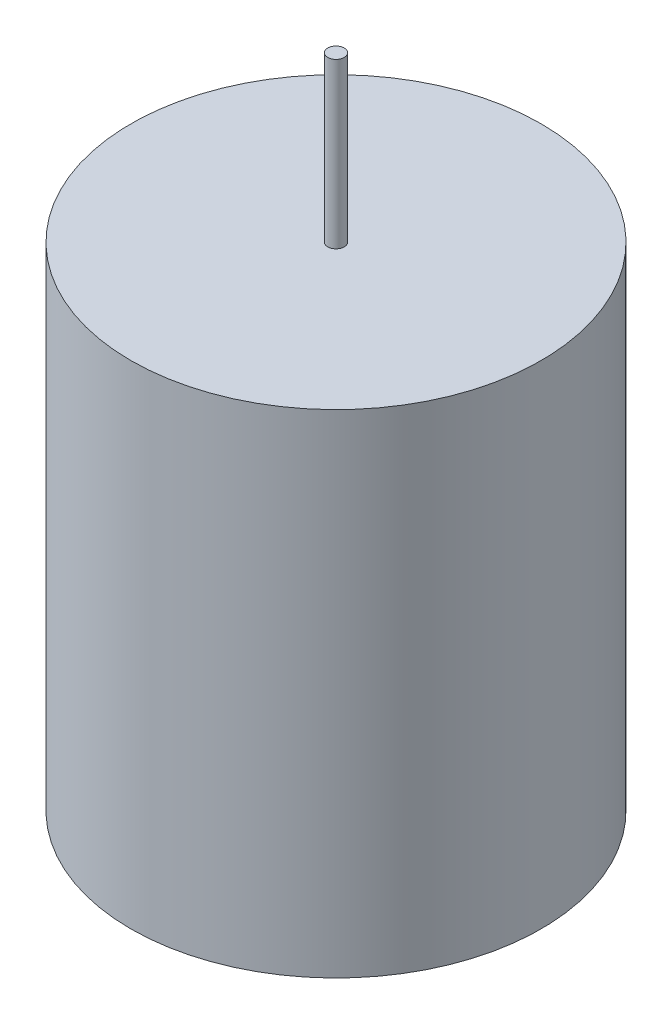
SolidWorks part; units mm, degrees
ref_plane "Front Plane" through (0, 0, 0) normal (0, 0, 1) x (1, 0, 0)
ref_plane "Top Plane" through (0, 0, 0) normal (0, 1, 0) x (1, 0, 0)
ref_plane "Right Plane" through (0, 0, 0) normal (1, 0, 0) x (0, 0, -1)
sketch "Sketch1" plane through (0, 0, 0) normal (0, 1, 0) x (1, 0, 0)
  circle A0 centre (0, 0) radius 12.5
  dimension "D1" = 25
extrude "Boss-Extrude1" add sketch "Sketch1" along normal blind 30 contours A0
sketch "Sketch2" plane through (0, 30, 0) normal (0, 1, 0) x (1, 0, 0)
  circle A0 centre (0, 0) radius 0.5
  dimension "D1" = 1
extrude "Boss-Extrude2" add sketch "Sketch2" along normal blind 10 and the other way blind 35
